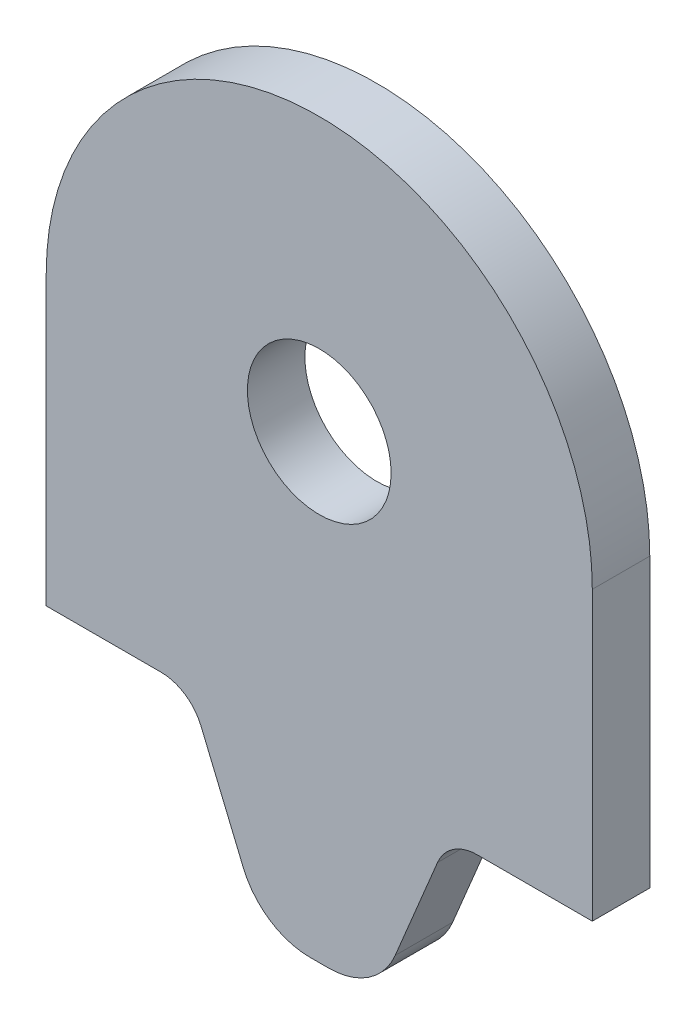
SolidWorks part; units mm, degrees
material "Foam"
ref_plane "Front Plane" through (0, 0, 0) normal (0, 0, 1) x (1, 0, 0)
ref_plane "Top Plane" through (0, 0, 0) normal (0, 1, 0) x (1, 0, 0)
ref_plane "Right Plane" through (0, 0, 0) normal (1, 0, 0) x (0, 0, -1)
sketch "Sketch1" plane through (0, 0, 0) normal (0, 0, 1) x (1, 0, 0)
  line L0 (-19, 0) -> (-19, -32)
  line L1 (-14.8, -45) -> (-5, -45)
  line L2 (19, -45) -> (19, 0)
  line L3 (0, 0) -> (0, -42) construction
  line L4 (5, -42) -> (-5, -42)
  line L5 (-5, -42) -> (-5, -45)
  line L6 (5, -42) -> (5, -45)
  line L7 (5, -45) -> (19, -45)
  line L8 (-19, -32) -> (-14.8, -32)
  line L9 (-14.8, -32) -> (-14.8, -45)
  arc A0 (19, 0) -> (-19, 0) centre (0, 0) ccw
  circle A1 centre (0, 0) radius 2.5
  arc A2 (-19, 0) -> (19, 0) centre (0, 0) ccw construction
  circle A3 centre (-14, -27) radius 1.5
  circle A6 centre (14, -27) radius 1.5
  dimension "D3" = 38
  dimension "D4" = 18
  dimension "D2" = 45
  dimension "D8" = 5
  dimension "D1" = 3
  dimension "D5" = 5
  dimension "D6" = 5
  dimension "D9" = 3
  dimension "D10" = 10
  dimension "D11" = 4.2
  dimension "D12" = 13
extrude "Boss-Extrude1" add sketch "Sketch1" along normal blind 4
sketch "Sketch2" plane through (0, 0, 4) normal (0, 0, 1) x (1, 0, 0)
  line L0 (-19, -20) -> (-9, -20)
  line L1 (-19, 0) -> (-19, -32) construction
  line L2 (-9, -20) -> (-9, -32) construction
  line L3 (-4, -32) -> (4, -32)
  line L4 (-9, -32) -> (-4, -32) construction
  line L5 (9, -20) -> (19, -20)
  line L6 (19, -45) -> (19, 0) construction
  line L7 (0, 0) -> (0, -32) construction
  line L9 (-19, -20) -> (-19, -45)
  line L10 (-19, -45) -> (19, -45)
  line L11 (19, -45) -> (19, -20)
  line L12 (-9, -20) -> (-4, -32)
  line L13 (4, -32) -> (9, -20)
  line L14 (4, -32) -> (9, -32) construction
  line L15 (9, -32) -> (9, -20) construction
  line L16 (-5, -42) -> (5, -42) construction
  circle A0 centre (0, 0) radius 5
  dimension "D1" = 10
  dimension "D2" = 12
  dimension "D3" = 10
  dimension "D4" = 10
  dimension "D5" = 5
extrude "Cut-Extrude1" cut sketch "Sketch2" against normal through all
fillet "Fillet1" radius 5 2 edges at (-4, -32, 2) (4, -32, 2)
fillet "Fillet2" radius 3 2 edges at (9, -20, 2) (-9, -20, 2)
